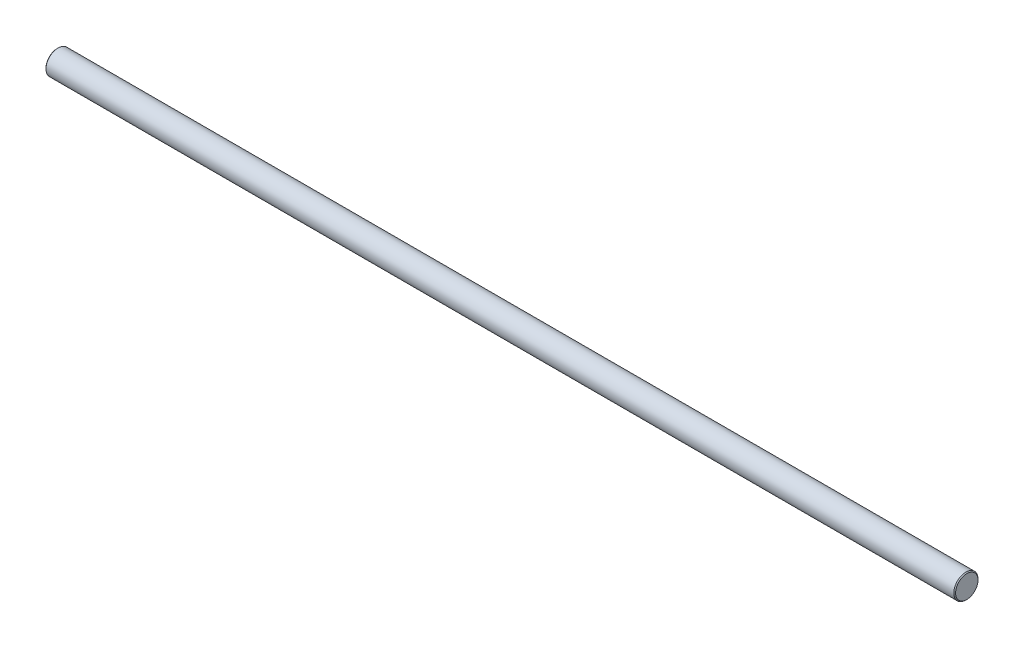
SolidWorks part; units mm, degrees
material "SUJ2"
ref_plane "Front Plane" through (0, 0, 0) normal (0, 0, 1) x (1, 0, 0)
ref_plane "Top Plane" through (0, 0, 0) normal (0, 1, 0) x (1, 0, 0)
ref_plane "Right Plane" through (0, 0, 0) normal (1, 0, 0) x (0, 0, -1)
sketch "Sketch1" plane through (0, 0, 0) normal (0, 0, 1) x (1, 0, 0)
  line L0 (0, 0) -> (300, 0) construction
  line L2 (0, 0) -> (300, 0)
  line L3 (0, 0) -> (0, 4)
  line L4 (0, 4) -> (300, 4)
  line L5 (300, 0) -> (300, 4)
  dimension "D" = 8
  dimension "L" = 300
revolve "Revolve1" add sketch "Sketch1" angle 360 about L0
chamfer "Chamfer1" distance 0.3 2 edges at (300, 0, 4) (0, 0, 4)
sketch "Sketch2" plane through (0, 0, 0) normal (0, 0, 1) x (1, 0, 0)
  line L0 (0, 0) -> (300, 0) construction
  line L1 (300, 0) -> (300, 4) construction
  line L2 (0, 0) -> (300, 0)
  line L3 (0, 0) -> (0, 1.25)
  line L4 (0, 1.25) -> (300, 1.25)
  line L5 (300, 0) -> (300, 1.25)
  dimension "D_s" = 2.5
revolve "Cut-Revolve1" [suppressed] cut sketch "Sketch2" angle 360 about L0
